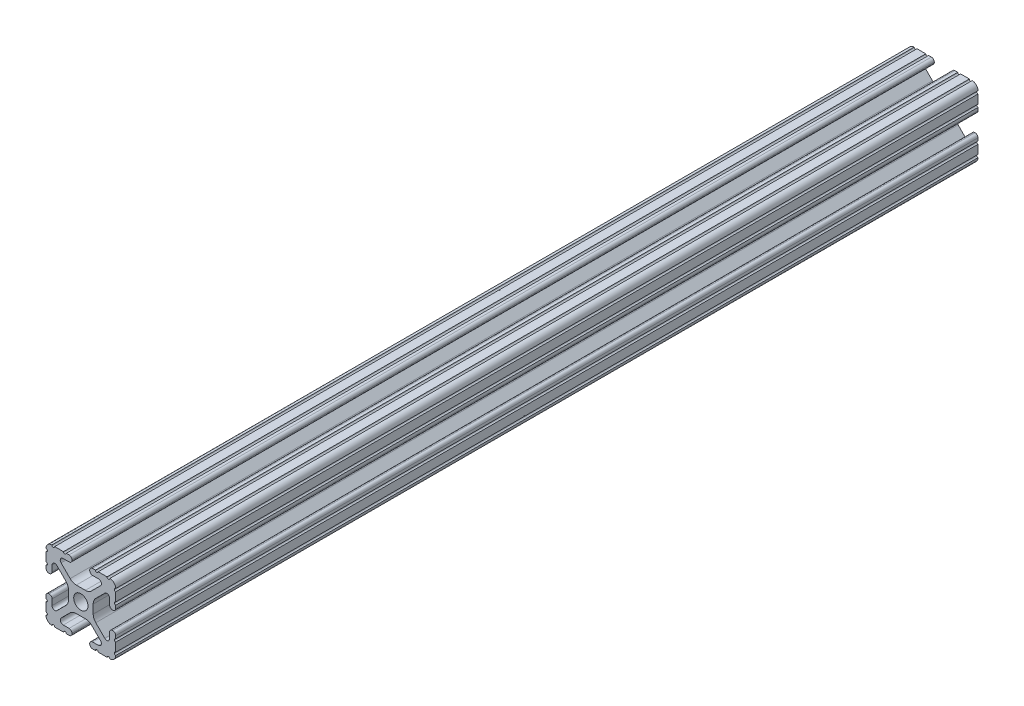
SolidWorks part; units mm, degrees
ref_plane "Front Plane" through (0, 0, 0) normal (0, 0, 1) x (1, 0, 0)
ref_plane "Top Plane" through (0, 0, 0) normal (0, 1, 0) x (1, 0, 0)
ref_plane "Right Plane" through (0, 0, 0) normal (1, 0, 0) x (0, 0, -1)
sketch "Sketch1" plane through (0, 0, 0) normal (0, 0, 1) x (1, 0, 0)
  line L88 (-7.1797, -8.6452) -> (-3.9523, -5.4237)
  line L89 (-1.7093, -4.4958) -> (1.7093, -4.4958)
  line L90 (3.9523, -5.4237) -> (7.1797, -8.6452)
  line L91 (6.4164, -10.4902) -> (4.2875, -10.4902)
  line L92 (3.2385, -11.5392) -> (3.2385, -11.651)
  line L93 (4.2875, -12.7) -> (5.3171, -12.7)
  line L94 (6.3331, -12.7) -> (9.5504, -12.7)
  line L95 (12.7, -9.5504) -> (12.7, -6.3331)
  line L96 (12.7, -5.3171) -> (12.7, -4.2875)
  line L97 (11.651, -3.2385) -> (11.5392, -3.2385)
  line L98 (10.4902, -4.2875) -> (10.4902, -6.4021)
  line L99 (8.7371, -7.1294) -> (5.441, -3.8408)
  line L100 (4.5085, -1.5932) -> (4.5085, 1.5932)
  line L101 (5.441, 3.8408) -> (8.7371, 7.1294)
  line L102 (10.4902, 6.4021) -> (10.4902, 4.2875)
  line L103 (11.5392, 3.2385) -> (11.651, 3.2385)
  line L104 (12.7, 4.2875) -> (12.7, 5.3171)
  line L105 (12.7, 6.3331) -> (12.7, 9.5504)
  line L106 (9.5504, 12.7) -> (6.3331, 12.7)
  line L107 (5.3171, 12.7) -> (4.2875, 12.7)
  line L108 (3.2385, 11.651) -> (3.2385, 11.5392)
  line L109 (4.2875, 10.4902) -> (6.4768, 10.4902)
  line L110 (7.207, 8.7244) -> (3.8983, 5.4232)
  line L111 (1.6558, 4.4958) -> (-1.6558, 4.4958)
  line L112 (-3.8983, 5.4232) -> (-7.207, 8.7244)
  line L113 (-6.4768, 10.4902) -> (-4.2875, 10.4902)
  line L114 (-3.2385, 11.5392) -> (-3.2385, 11.651)
  line L115 (-4.2875, 12.7) -> (-5.3171, 12.7)
  line L116 (-6.3331, 12.7) -> (-9.5504, 12.7)
  line L117 (-12.7, 9.5504) -> (-12.7, 6.3331)
  line L118 (-12.7, 5.3171) -> (-12.7, 4.2875)
  line L119 (-11.651, 3.2385) -> (-11.5392, 3.2385)
  line L120 (-10.4902, 4.2875) -> (-10.4902, 6.4021)
  line L121 (-8.7371, 7.1294) -> (-5.441, 3.8408)
  line L122 (-4.5085, 1.5932) -> (-4.5085, -1.5932)
  line L123 (-5.441, -3.8408) -> (-8.7371, -7.1294)
  line L124 (-10.4902, -6.4021) -> (-10.4902, -4.2875)
  line L125 (-11.5392, -3.2385) -> (-11.651, -3.2385)
  line L126 (-12.7, -4.2875) -> (-12.7, -5.3171)
  line L127 (-12.7, -6.3331) -> (-12.7, -9.5504)
  line L128 (-9.5504, -12.7) -> (-6.3331, -12.7)
  line L129 (-5.3171, -12.7) -> (-4.2875, -12.7)
  line L130 (-3.2385, -11.651) -> (-3.2385, -11.5392)
  line L131 (-4.2875, -10.4902) -> (-6.4164, -10.4902)
  circle A1 centre (0, 0) radius 2.6035
  arc A104 (-7.1797, -8.6452) -> (-6.4164, -10.4902) centre (-6.4164, -9.4098) ccw
  arc A105 (-1.7093, -4.4958) -> (-3.9523, -5.4237) centre (-1.7093, -7.6708) ccw
  arc A106 (3.9523, -5.4237) -> (1.7093, -4.4958) centre (1.7093, -7.6708) ccw
  arc A107 (6.4164, -10.4902) -> (7.1797, -8.6452) centre (6.4164, -9.4098) ccw
  arc A108 (4.2875, -10.4902) -> (3.2385, -11.5392) centre (4.2875, -11.5392) ccw
  arc A109 (3.2385, -11.651) -> (4.2875, -12.7) centre (4.2875, -11.651) ccw
  arc A110 (6.3331, -12.7) -> (5.3171, -12.7) centre (5.8251, -12.7) ccw
  arc A111 (10.5664, -12.6998) -> (9.5504, -12.7) centre (10.0584, -12.7) ccw
  arc A112 (10.5664, -12.6998) -> (12.6998, -10.5664) centre (10.5918, -10.5918) ccw
  arc A113 (12.7, -9.5504) -> (12.6998, -10.5664) centre (12.7, -10.0584) ccw
  arc A114 (12.7, -5.3171) -> (12.7, -6.3331) centre (12.7, -5.8251) ccw
  arc A115 (12.7, -4.2875) -> (11.651, -3.2385) centre (11.651, -4.2875) ccw
  arc A116 (11.5392, -3.2385) -> (10.4902, -4.2875) centre (11.5392, -4.2875) ccw
  arc A117 (8.7371, -7.1294) -> (10.4902, -6.4021) centre (9.4628, -6.4021) ccw
  arc A118 (4.5085, -1.5932) -> (5.441, -3.8408) centre (7.6835, -1.5932) ccw
  arc A119 (5.441, 3.8408) -> (4.5085, 1.5932) centre (7.6835, 1.5932) ccw
  arc A120 (10.4902, 6.4021) -> (8.7371, 7.1294) centre (9.4628, 6.4021) ccw
  arc A121 (10.4902, 4.2875) -> (11.5392, 3.2385) centre (11.5392, 4.2875) ccw
  arc A122 (11.651, 3.2385) -> (12.7, 4.2875) centre (11.651, 4.2875) ccw
  arc A123 (12.7, 6.3331) -> (12.7, 5.3171) centre (12.7, 5.8251) ccw
  arc A124 (12.6998, 10.5664) -> (12.7, 9.5504) centre (12.7, 10.0584) ccw
  arc A125 (12.6998, 10.5664) -> (10.5664, 12.6998) centre (10.5918, 10.5918) ccw
  arc A126 (9.5504, 12.7) -> (10.5664, 12.6998) centre (10.0584, 12.7) ccw
  arc A127 (5.3171, 12.7) -> (6.3331, 12.7) centre (5.8251, 12.7) ccw
  arc A128 (4.2875, 12.7) -> (3.2385, 11.651) centre (4.2875, 11.651) ccw
  arc A129 (3.2385, 11.5392) -> (4.2875, 10.4902) centre (4.2875, 11.5392) ccw
  arc A130 (7.207, 8.7244) -> (6.4768, 10.4902) centre (6.4768, 9.4563) ccw
  arc A131 (1.6558, 4.4958) -> (3.8983, 5.4232) centre (1.6558, 7.6708) ccw
  arc A132 (-3.8983, 5.4232) -> (-1.6558, 4.4958) centre (-1.6558, 7.6708) ccw
  arc A133 (-6.4768, 10.4902) -> (-7.207, 8.7244) centre (-6.4768, 9.4563) ccw
  arc A134 (-4.2875, 10.4902) -> (-3.2385, 11.5392) centre (-4.2875, 11.5392) ccw
  arc A135 (-3.2385, 11.651) -> (-4.2875, 12.7) centre (-4.2875, 11.651) ccw
  arc A136 (-6.3331, 12.7) -> (-5.3171, 12.7) centre (-5.8251, 12.7) ccw
  arc A137 (-10.5664, 12.6998) -> (-9.5504, 12.7) centre (-10.0584, 12.7) ccw
  arc A138 (-10.5664, 12.6998) -> (-12.6998, 10.5664) centre (-10.5918, 10.5918) ccw
  arc A139 (-12.7, 9.5504) -> (-12.6998, 10.5664) centre (-12.7, 10.0584) ccw
  arc A140 (-12.7, 5.3171) -> (-12.7, 6.3331) centre (-12.7, 5.8251) ccw
  arc A141 (-12.7, 4.2875) -> (-11.651, 3.2385) centre (-11.651, 4.2875) ccw
  arc A142 (-11.5392, 3.2385) -> (-10.4902, 4.2875) centre (-11.5392, 4.2875) ccw
  arc A143 (-8.7371, 7.1294) -> (-10.4902, 6.4021) centre (-9.4628, 6.4021) ccw
  arc A144 (-4.5085, 1.5932) -> (-5.441, 3.8408) centre (-7.6835, 1.5932) ccw
  arc A145 (-5.441, -3.8408) -> (-4.5085, -1.5932) centre (-7.6835, -1.5932) ccw
  arc A146 (-10.4902, -6.4021) -> (-8.7371, -7.1294) centre (-9.4628, -6.4021) ccw
  arc A147 (-10.4902, -4.2875) -> (-11.5392, -3.2385) centre (-11.5392, -4.2875) ccw
  arc A148 (-11.651, -3.2385) -> (-12.7, -4.2875) centre (-11.651, -4.2875) ccw
  arc A149 (-12.7, -6.3331) -> (-12.7, -5.3171) centre (-12.7, -5.8251) ccw
  arc A150 (-12.6998, -10.5664) -> (-12.7, -9.5504) centre (-12.7, -10.0584) ccw
  arc A151 (-12.6998, -10.5664) -> (-10.5664, -12.6998) centre (-10.5918, -10.5918) ccw
  arc A152 (-9.5504, -12.7) -> (-10.5664, -12.6998) centre (-10.0584, -12.7) ccw
  arc A153 (-5.3171, -12.7) -> (-6.3331, -12.7) centre (-5.8251, -12.7) ccw
  arc A154 (-4.2875, -12.7) -> (-3.2385, -11.651) centre (-4.2875, -11.651) ccw
  arc A155 (-3.2385, -11.5392) -> (-4.2875, -10.4902) centre (-4.2875, -11.5392) ccw
extrude "Boss-Extrude1" add sketch "Sketch1" along normal mid plane 314.325
